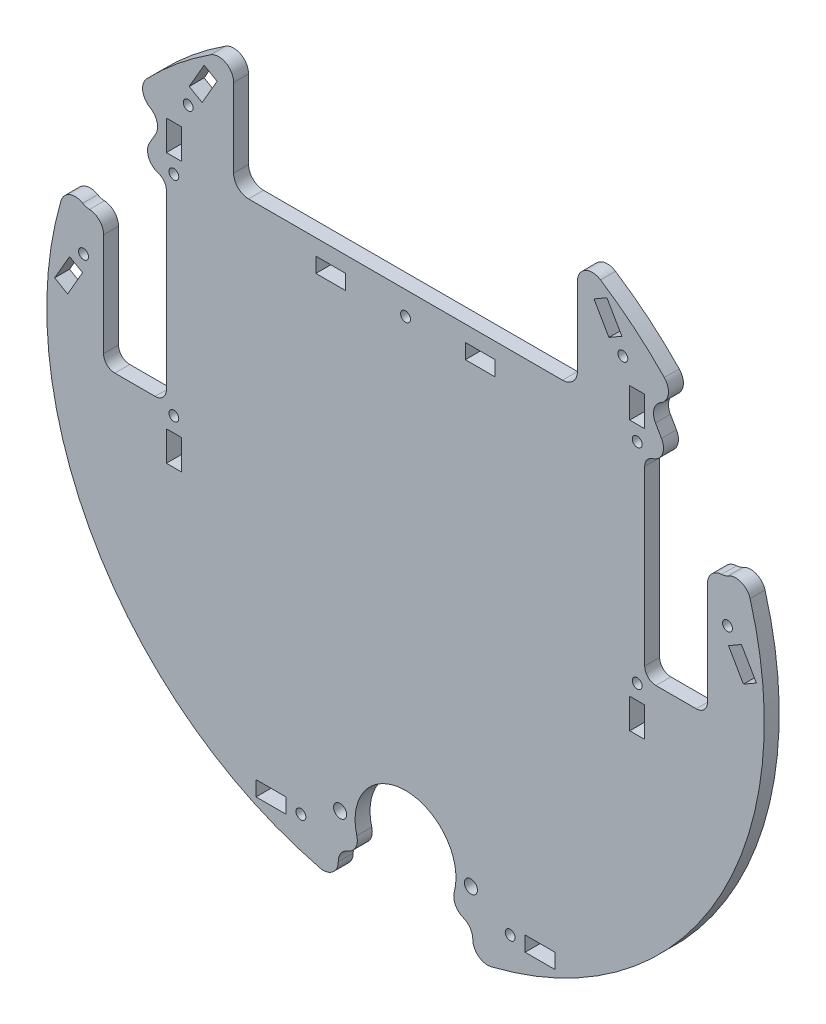
SolidWorks part; units mm, degrees
ref_plane "Front Plane" through (0, 0, 0) normal (0, 0, 1) x (1, 0, 0)
ref_plane "Top Plane" through (0, 0, 0) normal (0, 1, 0) x (1, 0, 0)
ref_plane "Right Plane" through (0, 0, 0) normal (1, 0, 0) x (0, 0, -1)
sketch "Sketch1" plane through (0, 0, 0) normal (0, 0, 1) x (1, 0, 0)
  circle A0 centre (0, 0) radius 152.4
  dimension "D1" = 304.8
extrude "Boss-Extrude1" add sketch "Sketch1" along normal blind 6.35
sketch "Sketch3" plane through (0, 0, 6.35) normal (0, 0, 1) x (1, 0, 0)
  line L0 (28.575, -135.4501) -> (-28.575, -135.4501)
  line L2 (-28.575, -135.4501) -> (-28.575, -173.5501)
  line L3 (-28.575, -173.5501) -> (28.575, -173.5501)
  line L4 (28.575, -173.5501) -> (28.575, -135.4501)
  line L5 (69.85, -135.4501) -> (-69.85, -135.4501) construction
  circle A0 centre (0, 0) radius 152.4 construction
  point P2 (0, -135.4501)
  dimension "D1" = 57.15
  dimension "D2" = 38.1
  dimension "D3" = 139.7
extrude "Cut-Extrude1" cut sketch "Sketch3" against normal blind 6.35
sketch "Sketch4" plane through (0, 0, 6.35) normal (0, 0, 1) x (1, 0, 0)
  line L0 (101.6, 107.95) -> (101.6, -44.45)
  line L1 (128.27, 31.75) -> (101.6, 31.75) construction
  line L2 (101.6, 73.025) -> (128.27, 73.025)
  line L3 (101.6, 73.025) -> (101.6, -9.525)
  line L4 (101.6, -9.525) -> (128.27, -9.525)
  line L5 (128.27, 73.025) -> (128.27, -9.525)
  point P9 (101.6, 31.75)
  arc M2 (28.575, -149.6971) -> (-28.575, -149.6971) centre (0, 0) ccw
  dimension "D1" = 152.4
  dimension "D2" = 82.55
  dimension "D3" = 31.75
  dimension "D4" = 26.67
  dimension "D5" = 101.6
extrude "Cut-Extrude2" cut sketch "Sketch4" against normal blind 6.35 contours L1 L2 L0 M2 | L1 L3 L4 M2
sketch "Sketch5" plane through (0, 0, 6.35) normal (0, 0, 1) x (1, 0, 0)
  line L0 (-75.6905, -132.2751) -> (75.6905, -132.2751) construction
  line L2 (0, -132.2751) -> (0, -151.0809) construction
  line L3 (-50.8, -135.4501) -> (-63.5, -135.4501)
  line L4 (-50.8, -135.4501) -> (-50.8, -129.1001)
  line L5 (-50.8, -129.1001) -> (-63.5, -129.1001)
  line L6 (-63.5, -135.4501) -> (-63.5, -129.1001)
  line L7 (-50.8, -135.4501) -> (-63.5, -129.1001) construction
  line L8 (-50.8, -129.1001) -> (-63.5, -135.4501) construction
  line L9 (50.8, -129.1001) -> (63.5, -135.4501) construction
  line L10 (50.8, -135.4501) -> (63.5, -129.1001) construction
  line L11 (63.5, -135.4501) -> (63.5, -129.1001)
  line L12 (50.8, -129.1001) -> (63.5, -129.1001)
  line L13 (50.8, -135.4501) -> (50.8, -129.1001)
  line L14 (50.8, -135.4501) -> (63.5, -135.4501)
  line L15 (28.575, -135.4501) -> (-28.575, -135.4501) construction
  line L16 (-63.5, -135.4501) -> (-69.85, -135.4501) construction
  circle A0 centre (-44.45, -132.2751) radius 2.0955
  circle A3 centre (44.45, -132.2751) radius 2.0955
  arc A4 (28.575, -149.6971) -> (-28.575, -149.6971) centre (0, 0) ccw construction
  point P6 (-57.15, -132.2751)
  point P29 (57.15, -132.2751)
  dimension "D2" = 4.191
  dimension "D1" = 3.175
  dimension "D3" = 12.7
  dimension "D4" = 6.35
  dimension "D5" = 6.35
  dimension "D6" = 69.85
extrude "Cut-Extrude3" cut sketch "Sketch5" against normal blind 6.35
sketch "Sketch6" plane through (0, 0, 6.35) normal (0, 0, 1) x (1, 0, 0)
  line L0 (98.425, 116.3541) -> (98.425, -69.6983) construction
  line L1 (101.6, 31.75) -> (58.7092, 31.75) construction
  line L2 (101.6, 73.025) -> (101.6, -9.525) construction
  line L3 (101.6, 73.025) -> (101.6, 101.6) construction
  line L4 (95.25, 95.25) -> (101.6, 95.25)
  line L5 (95.25, 95.25) -> (95.25, 82.55)
  line L6 (95.25, 82.55) -> (101.6, 82.55)
  line L7 (101.6, 95.25) -> (101.6, 82.55)
  line L8 (95.25, 95.25) -> (101.6, 82.55) construction
  line L9 (95.25, 82.55) -> (101.6, 95.25) construction
  line L10 (95.25, -19.05) -> (101.6, -31.75) construction
  line L11 (95.25, -31.75) -> (101.6, -19.05) construction
  line L12 (101.6, -31.75) -> (101.6, -19.05)
  line L13 (95.25, -19.05) -> (101.6, -19.05)
  line L14 (95.25, -31.75) -> (95.25, -19.05)
  line L15 (95.25, -31.75) -> (101.6, -31.75)
  arc A0 (28.575, -149.6971) -> (-28.575, -149.6971) centre (0, 0) ccw construction
  circle A1 centre (98.425, 76.2) radius 2.0955
  circle A2 centre (98.425, -12.7) radius 2.0955
  point P9 (98.425, 88.9)
  point P25 (98.425, -25.4)
  dimension "D4" = 4.191
  dimension "D1" = 3.175
  dimension "D2" = 12.7
  dimension "D3" = 6.35
  dimension "D5" = 6.35
  dimension "D6" = 69.85
extrude "Cut-Extrude4" cut sketch "Sketch6" against normal blind 6.35
sketch "Sketch7" plane through (0, 0, 6.35) normal (0, 0, 1) x (1, 0, 0)
  line L0 (0, 0) -> (0, 152.4) construction
  line L1 (73.025, 133.7651) -> (73.025, 82.9651)
  line L2 (73.025, 82.9651) -> (0, 82.9651)
  line L3 (0, 82.9651) -> (0, 215.7401)
  line L4 (0, 215.7401) -> (73.025, 133.7651)
  arc A0 (28.575, -149.6971) -> (-28.575, -149.6971) centre (0, 0) ccw construction
  dimension "D1" = 50.8
  dimension "D3" = 73.025
extrude "Cut-Extrude5" cut sketch "Sketch7" against normal blind 6.35
mirror "Mirror1" about plane through (0, 0, 0) normal (1, 0, 0) of "Cut-Extrude5", "Cut-Extrude2", "Cut-Extrude4"
pattern_circular "CirPattern1" count 3 every 120 about axis through (0, 0, 0) along (0, 0, 1) of "Cut-Extrude1", "Cut-Extrude3"
fillet "Fillet1" radius 6.35 12 edges at (-143.929, 50.1019, 3.175) (-131.5908, 42.9784, 3.175) (-115.354, 99.5952, 3.175) (-103.0158, 92.4717, 3.175) (103.0158, 92.4717, 3.175) (115.354, 99.5952, 3.175) (131.5908, 42.9784, 3.175) (143.929, 50.1019, 3.175) (28.575, -149.6971, 3.175) (28.575, -135.4501, 3.175) (-28.575, -149.6971, 3.175) (-28.575, -135.4501, 3.175)
fillet "Fillet2" radius 6.35 4 edges at (128.27, 48.7301, 3.175) (114.2433, 73.025, 3.175) (-128.27, 48.7301, 3.175) (-114.2433, 73.025, 3.175)
fillet "Fillet3" radius 4.7625 7 edges at (128.27, -9.525, 3.175) (101.6, -9.525, 3.175) (-128.27, -9.525, 3.175) (-101.6, -9.525, 3.175) (101.6, 73.025, 3.175) (-103.2448, 73.025, 3.175) (-101.6, 73.025, 3.175)
fillet "Fillet4" radius 6.35 4 edges at (-73.025, 133.7651, 3.175) (73.025, 133.7651, 3.175) (-73.025, 82.9651, 3.175) (73.025, 82.9651, 3.175)
sketch "Sketch8" plane through (0, 0, 0) normal (0, 0, -1) x (-1, 0, 0)
  circle A4 centre (-27.7812, -122.7501) radius 2.7781 construction
  circle A5 centre (27.7813, -122.7501) radius 2.7781 construction
  circle A6 centre (0, -122.7501) radius 21.4312 construction
  circle A7 centre (-27.7812, -122.7501) radius 2.7781
  circle A8 centre (27.7813, -122.7501) radius 2.7781
  circle A9 centre (0, -122.7501) radius 21.4313
extrude "Cut-Extrude6" cut sketch "Sketch8" against normal blind 6.35
fillet "Fillet5" radius 6.35 2 edges at (-17.2629, -135.4501, 3.175) (17.2629, -135.4501, 3.175)
sketch "Sketch9" plane through (0, 0, 0) normal (0, 0, -1) x (-1, 0, 0)
  line L0 (38.1, 76.2) -> (25.4, 76.2) construction
  line L1 (25.4, 76.2) -> (25.4, 69.85) construction
  line L2 (25.4, 69.85) -> (38.1, 69.85) construction
  line L3 (38.1, 69.85) -> (38.1, 76.2) construction
  line L4 (-25.4, 69.85) -> (-25.4, 76.2) construction
  line L5 (-25.4, 76.2) -> (-38.1, 76.2) construction
  line L6 (-38.1, 69.85) -> (-25.4, 69.85) construction
  line L7 (-38.1, 76.2) -> (-38.1, 69.85) construction
  line L8 (38.1, 76.2) -> (25.4, 76.2)
  line L9 (25.4, 76.2) -> (25.4, 69.85)
  line L10 (25.4, 69.85) -> (38.1, 69.85)
  line L11 (38.1, 69.85) -> (38.1, 76.2)
  line L12 (-25.4, 69.85) -> (-25.4, 76.2)
  line L13 (-25.4, 76.2) -> (-38.1, 76.2)
  line L14 (-38.1, 69.85) -> (-25.4, 69.85)
  line L15 (-38.1, 76.2) -> (-38.1, 69.85)
  circle A0 centre (0, 73.025) radius 2.0955 construction
  circle A1 centre (0, 73.025) radius 2.0955
extrude "Cut-Extrude7" cut sketch "Sketch9" against normal up to next
